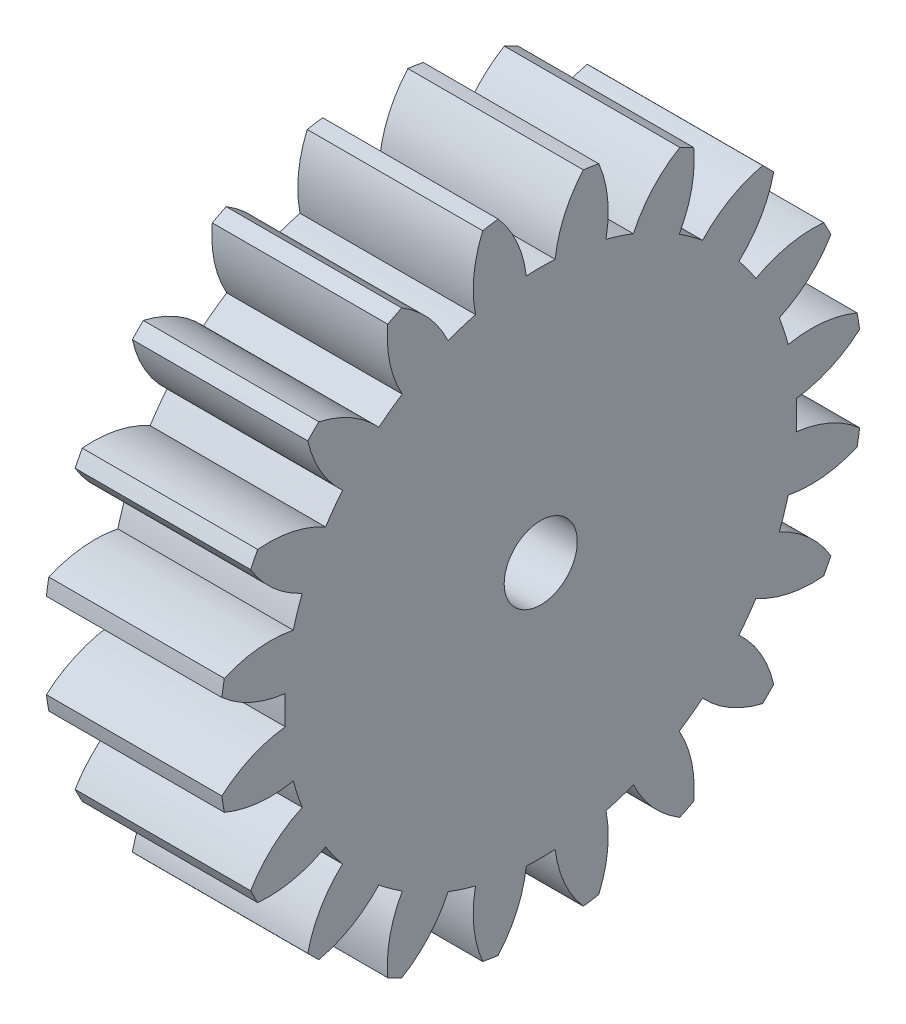
SolidWorks part; units mm, degrees
ref_plane "Plane1" through (0, 0, 0) normal (0, 0, 1) x (1, 0, 0)
ref_plane "Plane2" through (0, 0, 0) normal (0, 1, 0) x (1, 0, 0)
ref_plane "Plane3" through (0, 0, 0) normal (1, 0, 0) x (0, 0, -1)
other "Configuration Table"
sketch "HoldingSke" plane through (0, 0, 0) normal (0, 1, 0) x (1, 0, 0)
  line L0 (0, 0) -> (0.4698, -0.171)
  line L1 (-15, 0) -> (100, 0) construction
  line L2 (0, 0) -> (-2.1039, 2.3779)
  line L3 (0, 0) -> (-11.863, 4.5341)
  line L4 (0, 0) -> (8.1152, 2.9537)
  line L5 (0, 0) -> (-46.8476, -17.4728)
  line L6 (0, 0) -> (-9.9476, -6.7116)
  line L7 (-2.1039, 2.3779) -> (8.6586, 51.2059)
  line L8 (-76.2, 54.61) -> (-75.3, 54.61)
  line L9 (-71.009, 38.7566) -> (-53.1078, 45.2721)
  line L10 (-76.2, 71.12) -> (104.1128, 71.12)
  line L11 (0, 0) -> (-12, 0)
  line L12 (-76.2, 101.6) -> (-76.133, 101.6)
  line L13 (24.9733, 27.94) -> (52.9518, 28.4284)
  line L14 (24.9733, 27.94) -> (24.9743, 27.94)
  line L15 (24.9733, 27.94) -> (100.4006, 29.5858)
  line L16 (-63.627, -2) -> (-12.827, -2)
  circle A0 centre (0, 0) radius 2.5
  circle A1 centre (0, 0) radius 17.499
  circle A2 centre (0, 0) radius 37.5
  circle A3 centre (0, 0) radius 2.5
  dimension "MHD" = 34.998
  dimension "Hub_dia" = 75
  dimension "Bore" = 5
  dimension "MBD" = 5
  dimension "Num_teeth" = 20
  dimension "Pitch" = 0.5
  dimension "Overall_len" = 50
  dimension "Show_teeth" = 20
  dimension "Thickness" = 12
  dimension "OAL" = 50.0001
  dimension "T_dim" = 0.9
  dimension "Ap" = 20
  dimension "H" = 19.05
  dimension "Pitch_radius" = 180.3128
  dimension "Width" = 12
  dimension "Backlash" = 0.067
  dimension "Addendum_fac" = 1
  dimension "Dedendum_fac" = 1.25
  dimension "Clearance_fac" = 0.25
  dimension "Dedendum_add" = 0.001
  dimension "Module" = 2
sketch "BasProSke" plane through (0, 0, 0) normal (0, 1, 0) x (1, 0, 0)
  line L0 (-10, 0) -> (60, 0) construction
  line L1 (0, 0) -> (0, 22)
  line L2 (0, 0) -> (12, 0)
  line L3 (12, 0) -> (12, 22)
  line L4 (12, 22) -> (0, 22)
  dimension "Thickness" = 12
  dimension "Diameter" = 44
revolve "Base-Revolve" add sketch "BasProSke" angle 360 about L0
sketch "TooCutSke" plane through (0, 0, 0) normal (1, 0, 0) x (0, 0, -1)
  line L1 (0, 0) -> (0, 107) construction
  line L2 (0, 0) -> (-1.6864, 19.9288) construction
  line L3 (0, 0) -> (-6.2409, 39.4033) construction
  line L4 (-1.6864, 19.9288) -> (-3.1204, 19.7016) construction
  arc A0 (0.9862, 17.4712) -> (-0.9862, 17.4712) centre (0, 0) ccw
  arc A1 (2.9329, 21.8293) -> (-2.9329, 21.8293) centre (0, 0) ccw
  circle A2 centre (0, 0) radius 20 construction
  circle A3 centre (0, 0) radius 18.7939 construction
  arc A4 (-0.9862, 17.4712) -> (-2.9329, 21.8293) centre (-8.9313, 16.536) ccw
  arc A5 (2.9329, 21.8293) -> (0.9862, 17.4712) centre (8.9313, 16.536) ccw
  dimension "Root_dia" = 34.998
  dimension "Overcut_dia" = 44.0508
  dimension "Pitch_dia" = 40
  dimension "Base_dia" = 37.5877
  dimension "Flank_rad" = 8
  dimension "Half_ang" = 9
  dimension "Half_CT" = 1.4519
extrude "ToothCut" cut sketch "TooCutSke" along normal through all
fillet "Breaks" [suppressed] radius 0.04
fillet "RootFillets" [suppressed] radius 0.501
pattern_circular "TeethCuts" count 20 every 18 about axis through (-10, 0, 0) along (1, 0, 0) of "ToothCut", "RootFillets", "Breaks"
sketch "HubNeaOneSke" plane through (0, 0, 0) normal (-1, 0, 0) x (0, 0, 1)
  circle A0 centre (0, 0) radius 17.499
  dimension "Diameter" = 34.998
extrude "HubNearOne" [suppressed] add sketch "HubNeaOneSke" along normal blind 38.0001
sketch "HubNeaBotSke" plane through (0, 0, 0) normal (-1, 0, 0) x (0, 0, 1)
  circle A0 centre (0, 0) radius 17.499
  dimension "Diameter" = 34.998
extrude "HubNearBoth" [suppressed] add sketch "HubNeaBotSke" along normal blind 19
ref_plane "FarPln" through (12, 0, 0) normal (1, 0, 0) x (0, 0, -1)
sketch "HubFarSke" plane through (12, 0, 0) normal (1, 0, 0) x (0, 0, -1)
  circle A0 centre (0, 0) radius 17.499
  dimension "Diameter" = 34.998
extrude "HubFar" [suppressed] add sketch "HubFarSke" along normal blind 19
sketch "BorSke" plane through (0, 0, 0) normal (1, 0, 0) x (0, 0, -1)
  circle A0 centre (0, 0) radius 2.5
  dimension "Diameter" = 5
extrude "Bore" cut sketch "BorSke" along normal mid plane 100.0001
sketch "KeySke" plane through (0, 0, 0) normal (1, 0, 0) x (0, 0, -1)
  line L0 (-1, 0) -> (-1, 3.4)
  line L1 (-1, 3.4) -> (1, 3.4)
  line L2 (1, 3.4) -> (1, 0)
  line L3 (0, 0) -> (0, 34) construction
  line L4 (-1, 0) -> (1, 0)
  dimension "Offset" = 3.4
  dimension "Width" = 2
extrude "Keyway" [suppressed] cut sketch "KeySke" along normal mid plane 100.0001
pattern_circular "Keyway2" [suppressed] count 2 every 90 about axis through (-10, 0, 0) along (1, 0, 0)
equation "' \"Module@HoldingSke\" = 6.35"
equation "' \"Num_teeth@HoldingSke\" = 12"
equation "' \"Ap@HoldingSke\" =  20"
equation "' \"Ap@HoldingSke\" = 20"
equation "' \"Width@HoldingSke\" = 0.5 * 25.4"
equation "' \"Hub_dia@HoldingSke\"= 1 * 25.4"
equation "' \"Hub_dia@HoldingSke\" = 1 * 25.4"
equation "' \"Overall_len@HoldingSke\" = 1.0 * 25.4"
equation "' \"Bore@HoldingSke\" = 0.75 * 25.4"
equation "' \"T_dim@HoldingSke\" = 0.1 * 25.4"
equation "' \"Width@KeySke\" = 0.25 * 25.4"
equation "' \"Show_teeth@HoldingSke\" = 13"
equation "' \"Backlash@HoldingSke\" = 0.009 * 25.4"
equation "' \"Addendum_fac@HoldingSke\" = 1.0"
equation "' \"Dedendum_fac@HoldingSke\" = 1.25"
equation "' \"Dedendum_add@HoldingSke\" = 0.00005 * 25.4"
equation "' \"Clearance_fac@HoldingSke\" = 0.25"
equation "\"Pitch@HoldingSke\" = 1 / \"Module@HoldingSke\""
equation "\"Overcut_dia@TooCutSke\" = (\"Num_teeth@HoldingSke\" + 2 * \"Addendum_fac@HoldingSke\") / \"Pitch@HoldingSke\" + 0.002 * 25.4"
equation "\"Pitch_dia@TooCutSke\" = \"Num_teeth@HoldingSke\" / \"Pitch@HoldingSke\""
equation "\"Base_dia@TooCutSke\" = \"Num_teeth@HoldingSke\" / \"Pitch@HoldingSke\" * cos((\"Ap@HoldingSke\"  * 3.14159265 / 180))"
equation "\"Root_dia@TooCutSke\" = (\"Num_teeth@HoldingSke\" + 2) / \"Pitch@HoldingSke\" - 2 * (\"Addendum_fac@HoldingSke\" + \"Dedendum_fac@HoldingSke\") / \"Pitch@HoldingSke\" - \"Dedendum_add@HoldingSke\" * 2"
equation "\"Half_ang@TooCutSke\" = 180 / \"Num_teeth@HoldingSke\""
equation "\"Half_CT@TooCutSke\" = \"Num_teeth@HoldingSke\" / \"Pitch@HoldingSke\" * sin((3.14159265 / 2 / \"Num_teeth@HoldingSke\")) / 2 - 7 * \"Backlash@HoldingSke\" / 4"
equation "\"Flank_rad@TooCutSke\" = \"Num_teeth@HoldingSke\" / \"Pitch@HoldingSke\" / 5"
equation "\"Radius@RootFillets\" = \"Clearance_fac@HoldingSke\" / \"Pitch@HoldingSke\" + \"Dedendum_add@HoldingSke\""
equation "\"Break_rad@Breaks\" = 0.02 / \"Pitch@HoldingSke\""
equation "\"Thickness@HoldingSke\" = \"Width@HoldingSke\""
equation "\"OAL@HoldingSke\" = \"Thickness@HoldingSke\""
equation "\"MHD@HoldingSke\" = (\"Num_teeth@HoldingSke\" + 2) / \"Pitch@HoldingSke\" - 2 * (\"Addendum_fac@HoldingSke\" + \"Dedendum_fac@HoldingSke\")  / \"Pitch@HoldingSke\" - \"Dedendum_add@HoldingSke\" * 2"
equation "\"MBD@HoldingSke\" = (\"Num_teeth@HoldingSke\" + 2) / \"Pitch@HoldingSke\" - 2 * (\"Addendum_fac@HoldingSke\" + \"Dedendum_fac@HoldingSke\")  / \"Pitch@HoldingSke\" - \"Dedendum_add@HoldingSke\" * 2 - 0.002 * 25.4"
equation "\"MHD@HoldingSke\" = ((sgn( \"MHD@HoldingSke\" - \"Hub_dia@HoldingSke\" )-1)*( \"MHD@HoldingSke\" - \"Hub_dia@HoldingSke\" ))/-2+ \"Hub_dia@HoldingSke\""
equation "\"MBD@HoldingSke\" = ((sgn( \"MBD@HoldingSke\" - \"Bore@HoldingSke\" )-1)*( \"MBD@HoldingSke\" - \"Bore@HoldingSke\" ))/-2+ \"Bore@HoldingSke\""
equation "\"OAL@HoldingSke\" = ((sgn( \"OAL@HoldingSke\" - \"Overall_len@HoldingSke\" )+1)*( \"OAL@HoldingSke\" - \"Overall_len@HoldingSke\" ))/2 + \"Overall_len@HoldingSke\" + 0.000002 * 25.4"
equation "\"Num_teeth@TeethCuts\" = int( \"Show_teeth@HoldingSke\" ) + 1"
equation "\"Num_teeth@TeethCuts\" = ((sgn( \"Num_teeth@TeethCuts\" - \"Num_teeth@HoldingSke\" )-1)*( \"Num_teeth@TeethCuts\" - \"Num_teeth@HoldingSke\" ))/-2+ \"Num_teeth@HoldingSke\""
equation "\"Num_teeth@TeethCuts\" = ((sgn( \"Num_teeth@TeethCuts\" - 2.0)+1)*( \"Num_teeth@TeethCuts\" - 2.0))/2 +2.0"
equation "\"Angle@TeethCuts\" = 360.0 / \"Num_teeth@HoldingSke\""
equation "\"Diameter@BasProSke\" = (\"Num_teeth@HoldingSke\" + 2 * \"Addendum_fac@HoldingSke\") / \"Pitch@HoldingSke\""
equation "\"Thickness@BasProSke\"  = \"Thickness@HoldingSke\""
equation "' \"Fillet_rad@BasProSke\" =  \"Thickness@HoldingSke\" * 0.05"
equation "' \"Fillet_rad@BasProSke\" = \"Thickness@HoldingSke\" * 0.05"
equation "\"MHD@HoldingSke\" = ((sgn( \"MHD@HoldingSke\" - \"Root_dia@TooCutSke\" )-1)*( \"MHD@HoldingSke\" - \"Root_dia@TooCutSke\" ))/-2+ \"Root_dia@TooCutSke\""
equation "\"Diameter@HubNeaOneSke\" = \"MHD@HoldingSke\""
equation "\"Length@HubNearOne\" = \"OAL@HoldingSke\" - \"Thickness@BasProSke\""
equation "\"Diameter@HubNeaBotSke\" = \"MHD@HoldingSke\""
equation "\"Length@HubNearBoth\" = ( \"OAL@HoldingSke\" - \"Thickness@BasProSke\" ) / 2.0"
equation "\"Thickness@FarPln\" = \"Thickness@BasProSke\""
equation "\"Diameter@HubFarSke\" = \"MHD@HoldingSke\""
equation "\"Length@HubFar\" = ( \"OAL@HoldingSke\" - \"Thickness@BasProSke\" ) / 2.0"
equation "\"Diameter@BorSke\" = \"MBD@HoldingSke\""
equation "\"D1@Bore\" = \"OAL@HoldingSke\" * 2.0"
equation "\"D1@Keyway\" = \"OAL@HoldingSke\" * 2.0"
equation "\"Offset@KeySke\" = \"T_dim@HoldingSke\" + \"MBD@HoldingSke\" / 2.0"
